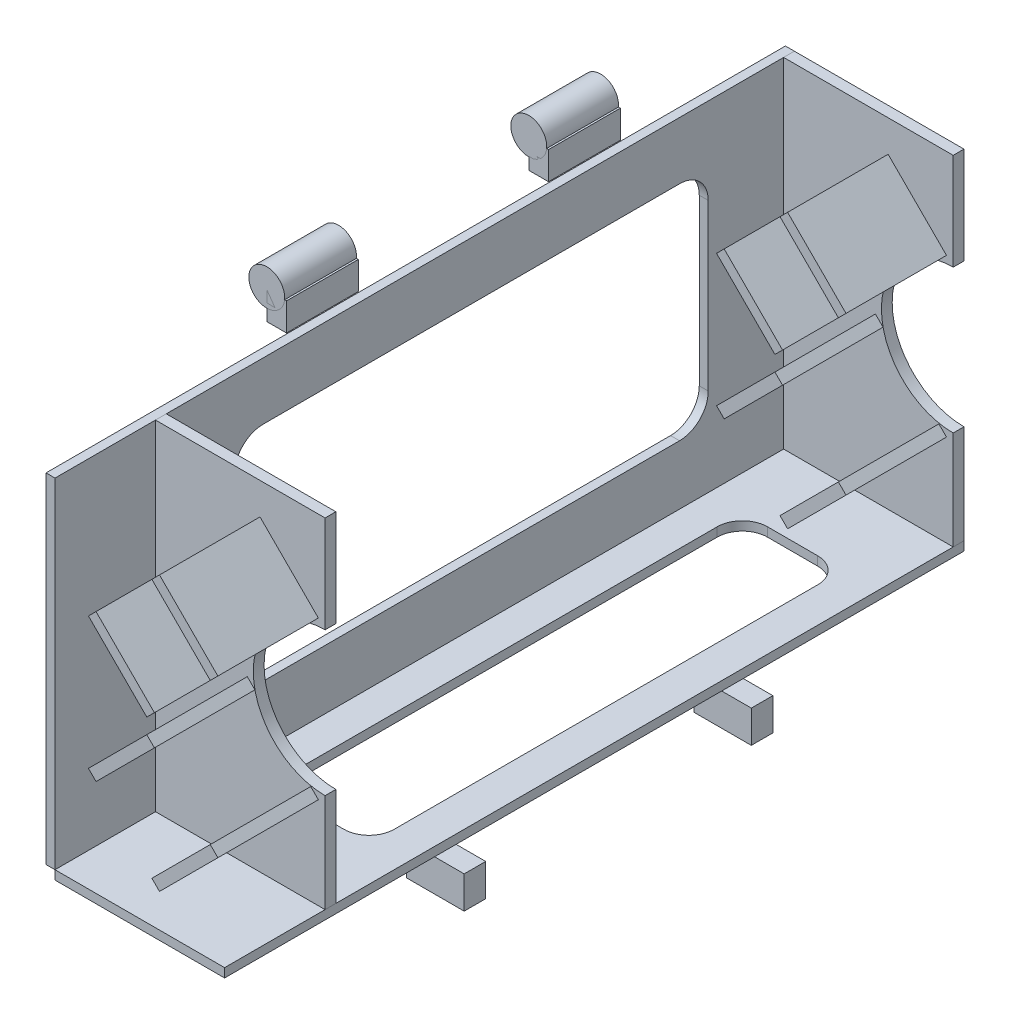
SolidWorks part; units mm, degrees
material "6061-T6 (SS)"
ref_plane "Front Plane" through (0, 0, 0) normal (0, 0, 1) x (1, 0, 0)
ref_plane "Top Plane" through (0, 0, 0) normal (0, 1, 0) x (1, 0, 0)
ref_plane "Right Plane" through (0, 0, 0) normal (1, 0, 0) x (0, 0, -1)
sketch "Extrude sketch 1" plane through (0, 0, 0) normal (0, 0, 1) x (1, 0, 0)
  line L0 (-95, 94) -> (-95, -95)
  line L1 (-95, -95) -> (-0.5, -95)
  line L2 (-0.5, -95) -> (-0.5, -40)
  line L3 (-0.5, 40) -> (-0.5, 94)
  line L4 (-0.5, 94) -> (-95, 94)
  arc A0 (-0.5, -40) -> (-0.5, 40) centre (-0.5, 0) cw
  dimension "D1" = 40
  dimension "D2" = 94.5
  dimension "D3" = 94
  dimension "D4" = 189
extrude "Extrude 1" add sketch "Extrude sketch 1" along normal blind 6 from offset 180 separate body
sketch "Extrude sketch 2" plane through (0, 0, 0) normal (0, 0, 1) x (1, 0, 0)
  line L0 (-39.598, 8.4853) -> (-72.1249, 41.0122)
  line L1 (-72.1249, 41.0122) -> (-76.3675, 36.7696)
  line L2 (-76.3675, 36.7696) -> (-43.8406, 4.2426)
  line L3 (-43.8406, 4.2426) -> (-39.598, 8.4853)
  dimension "D1" = 4.2426
  dimension "D2" = 32.5269
  dimension "D3" = 4.2426
extrude "Extrude 2" add sketch "Extrude sketch 2" along normal blind 56 from offset 186 separate body
sketch "Extrude sketch 3" plane through (0, 0, 0) normal (0, 0, 1) x (1, 0, 0)
  line L0 (-41.0122, 72.1249) -> (-8.4853, 39.598)
  line L1 (-8.4853, 39.598) -> (-4.2426, 43.8406)
  line L2 (-4.2426, 43.8406) -> (-36.7696, 76.3675)
  line L3 (-36.7696, 76.3675) -> (-41.0122, 72.1249)
  dimension "D1" = 4.2426
  dimension "D2" = 32.5269
  dimension "D3" = 4.2426
extrude "Extrude 3" add sketch "Extrude sketch 3" along normal blind 56 from offset 186 separate body
sketch "Extrude sketch 4" plane through (0, 0, 0) normal (0, 0, 1) x (1, 0, 0)
  line L0 (-8.4853, -39.598) -> (-41.0122, -72.1249)
  line L1 (-41.0122, -72.1249) -> (-36.7696, -76.3675)
  line L2 (-36.7696, -76.3675) -> (-4.2426, -43.8406)
  line L3 (-4.2426, -43.8406) -> (-8.4853, -39.598)
  dimension "D1" = 4.2426
  dimension "D2" = 32.5269
  dimension "D3" = 4.2426
extrude "Extrude 4" add sketch "Extrude sketch 4" along normal blind 56 from offset 186 separate body
sketch "Extrude sketch 5" plane through (0, 0, 0) normal (0, 0, 1) x (1, 0, 0)
  line L0 (-43.8406, -4.2426) -> (-76.3675, -36.7696)
  line L1 (-76.3675, -36.7696) -> (-72.1249, -41.0122)
  line L2 (-72.1249, -41.0122) -> (-39.598, -8.4853)
  line L3 (-39.598, -8.4853) -> (-43.8406, -4.2426)
  dimension "D1" = 4.2426
  dimension "D2" = 32.5269
  dimension "D3" = 4.2426
extrude "Extrude 5" add sketch "Extrude sketch 5" along normal blind 56 from offset 186 separate body
sketch "Extrude sketch 6" plane through (0, 0, 0) normal (0, 0, 1) x (1, 0, 0)
  line L0 (-95, 94) -> (-95, -95)
  line L1 (-95, -95) -> (-0.5, -95)
  line L2 (-0.5, -95) -> (-0.5, -40)
  line L3 (-0.5, 40) -> (-0.5, 94)
  line L4 (-0.5, 94) -> (-95, 94)
  arc A0 (-0.5, -40) -> (-0.5, 40) centre (-0.5, 0) cw
  dimension "D1" = 40
  dimension "D2" = 94.5
  dimension "D3" = 94
  dimension "D4" = 189
extrude "Extrude 6" add sketch "Extrude sketch 6" along normal blind 6 from offset 530 separate body
sketch "Extrude sketch 7" plane through (0, 0, 0) normal (0, 0, 1) x (1, 0, 0)
  line L0 (-39.598, 8.4853) -> (-72.1249, 41.0122)
  line L1 (-72.1249, 41.0122) -> (-76.3675, 36.7696)
  line L2 (-76.3675, 36.7696) -> (-43.8406, 4.2426)
  line L3 (-43.8406, 4.2426) -> (-39.598, 8.4853)
  dimension "D1" = 4.2426
  dimension "D2" = 32.5269
  dimension "D3" = 4.2426
extrude "Extrude 7" add sketch "Extrude sketch 7" along normal blind 56 from offset 536 separate body
sketch "Extrude sketch 8" plane through (0, 0, 0) normal (0, 0, 1) x (1, 0, 0)
  line L0 (-41.0122, 72.1249) -> (-8.4853, 39.598)
  line L1 (-8.4853, 39.598) -> (-4.2426, 43.8406)
  line L2 (-4.2426, 43.8406) -> (-36.7696, 76.3675)
  line L3 (-36.7696, 76.3675) -> (-41.0122, 72.1249)
  dimension "D1" = 4.2426
  dimension "D2" = 32.5269
  dimension "D3" = 4.2426
extrude "Extrude 8" add sketch "Extrude sketch 8" along normal blind 56 from offset 536 separate body
sketch "Extrude sketch 9" plane through (0, 0, 0) normal (0, 0, 1) x (1, 0, 0)
  line L0 (-8.4853, -39.598) -> (-41.0122, -72.1249)
  line L1 (-41.0122, -72.1249) -> (-36.7696, -76.3675)
  line L2 (-36.7696, -76.3675) -> (-4.2426, -43.8406)
  line L3 (-4.2426, -43.8406) -> (-8.4853, -39.598)
  dimension "D1" = 4.2426
  dimension "D2" = 32.5269
  dimension "D3" = 4.2426
extrude "Extrude 9" add sketch "Extrude sketch 9" along normal blind 56 from offset 536 separate body
sketch "Extrude sketch 10" plane through (0, 0, 0) normal (0, 0, 1) x (1, 0, 0)
  line L0 (-43.8406, -4.2426) -> (-76.3675, -36.7696)
  line L1 (-76.3675, -36.7696) -> (-72.1249, -41.0122)
  line L2 (-72.1249, -41.0122) -> (-39.598, -8.4853)
  line L3 (-39.598, -8.4853) -> (-43.8406, -4.2426)
  dimension "D1" = 4.2426
  dimension "D2" = 32.5269
  dimension "D3" = 4.2426
extrude "Extrude 10" add sketch "Extrude sketch 10" along normal blind 56 from offset 536 separate body
sketch "Extrude sketch 11" plane through (0, 0, 0) normal (1, 0, 0) x (0, 0, -1)
  line L0 (-180, 94) -> (-592, 94)
  line L1 (-592, 94) -> (-592, -95)
  line L2 (-592, -95) -> (-180, -95)
  line L3 (-180, -95) -> (-180, 94)
  line L4 (-244, 62) -> (-476, 62)
  line L5 (-492, 46) -> (-492, -46)
  line L6 (-476, -62) -> (-244, -62)
  line L7 (-228, -46) -> (-228, 46)
  arc A0 (-476, 62) -> (-492, 46) centre (-476, 46) ccw
  arc A1 (-492, -46) -> (-476, -62) centre (-476, -46) ccw
  arc A2 (-244, -62) -> (-228, -46) centre (-244, -46) ccw
  arc A3 (-228, 46) -> (-244, 62) centre (-244, 46) ccw
  dimension "D1" = 16
  dimension "D2" = 48
  dimension "D3" = 312
  dimension "D4" = 412
  dimension "D5" = 32
  dimension "D6" = 156
  dimension "D7" = 189
extrude "Extrude 11" add sketch "Extrude sketch 11" along normal blind 5 from offset 100 separate body
sketch "Extrude sketch 12" plane through (0, 0, 0) normal (0, 1, 0) x (1, 0, 0)
  line L0 (-0.5, -180) -> (-0.5, -592)
  line L1 (-0.5, -592) -> (-95, -592)
  line L2 (-95, -592) -> (-95, -180)
  line L3 (-95, -180) -> (-0.5, -180)
  line L4 (-20, -242) -> (-20, -478)
  line L5 (-34, -492) -> (-62, -492)
  line L6 (-76, -478) -> (-76, -242)
  line L7 (-62, -228) -> (-34, -228)
  arc A0 (-20, -478) -> (-34, -492) centre (-34, -478) cw
  arc A1 (-62, -492) -> (-76, -478) centre (-62, -478) cw
  arc A2 (-76, -242) -> (-62, -228) centre (-62, -242) cw
  arc A3 (-34, -228) -> (-20, -242) centre (-34, -242) cw
  dimension "D1" = 14
  dimension "D2" = 19.5
  dimension "D3" = 75.5
  dimension "D4" = 94.5
  dimension "D5" = 48
  dimension "D6" = 312
  dimension "D7" = 412
extrude "Extrude 12" add sketch "Extrude sketch 12" along normal blind 5 from offset 100 separate body
sketch "Extrude sketch 13" plane through (0, 0, 0) normal (0, 0, 1) x (1, 0, 0)
  circle A0 centre (-111, 111) radius 10
  dimension "D1" = 20
extrude "Extrude 13" add sketch "Extrude sketch 13" along normal blind 40 from offset 272 separate body
sketch "Extrude sketch 14" plane through (0, 0, 0) normal (0, 0, 1) x (1, 0, 0)
  line L0 (-100, 94.5) -> (-100, 110)
  line L1 (-100, 110) -> (-111, 110)
  line L2 (-111, 110) -> (-111, 94.5)
  line L3 (-111, 94.5) -> (-100, 94.5)
  dimension "D1" = 11
  dimension "D2" = 15.5
extrude "Extrude 14" add sketch "Extrude sketch 14" along normal blind 40 from offset 272 separate body
sketch "Extrude sketch 15" plane through (0, 0, 0) normal (0, 0, 1) x (1, 0, 0)
  circle A0 centre (-111, 111) radius 10
  dimension "D1" = 20
extrude "Extrude 15" add sketch "Extrude sketch 15" along normal blind 40 from offset 418 separate body
sketch "Extrude sketch 16" plane through (0, 0, 0) normal (0, 0, 1) x (1, 0, 0)
  line L0 (-100, 94.5) -> (-100, 110)
  line L1 (-100, 110) -> (-111, 110)
  line L2 (-111, 110) -> (-111, 94.5)
  line L3 (-111, 94.5) -> (-100, 94.5)
  dimension "D1" = 11
  dimension "D2" = 15.5
extrude "Extrude 16" add sketch "Extrude sketch 16" along normal blind 40 from offset 418 separate body
sketch "Extrude sketch 17" plane through (0, 0, 0) normal (0, 0, 1) x (1, 0, 0)
  line L0 (-16, -118) -> (16, -118)
  line L1 (16, -118) -> (16, -100)
  line L2 (16, -100) -> (-16, -100)
  line L3 (-16, -100) -> (-16, -118)
  dimension "D1" = 32
  dimension "D2" = 18
extrude "Extrude 17" add sketch "Extrude sketch 17" along normal blind 12 from offset 303 separate body
sketch "Extrude sketch 18" plane through (0, 0, 0) normal (0, 0, 1) x (1, 0, 0)
  line L0 (-16, -118) -> (16, -118)
  line L1 (16, -118) -> (16, -100)
  line L2 (16, -100) -> (-16, -100)
  line L3 (-16, -100) -> (-16, -118)
  dimension "D1" = 32
  dimension "D2" = 18
extrude "Extrude 18" add sketch "Extrude sketch 18" along normal blind 12 from offset 463 separate body
